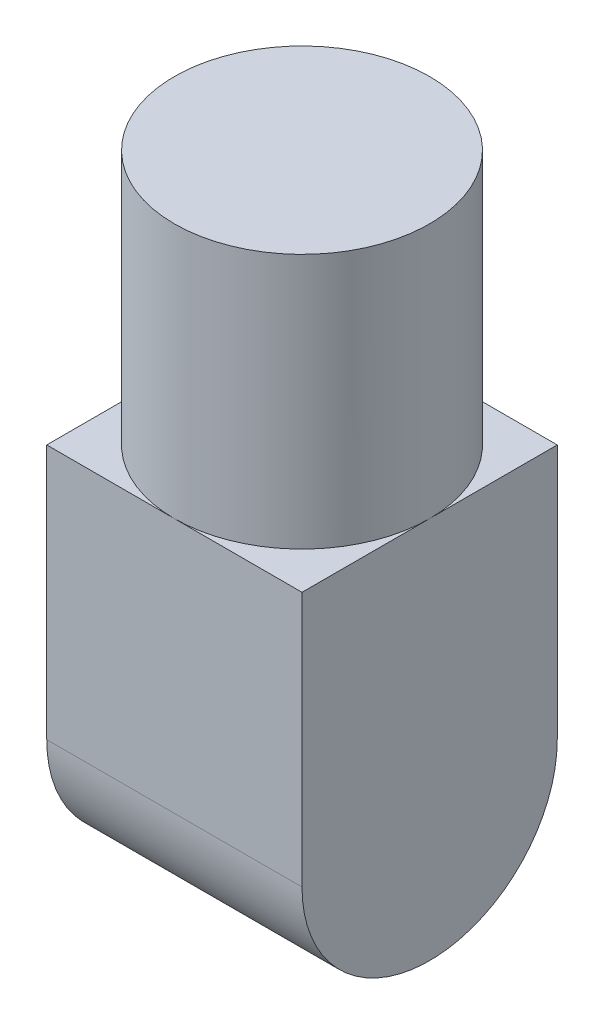
SolidWorks part; units mm, degrees
ref_plane "Front Plane" through (0, 0, 0) normal (0, 0, 1) x (1, 0, 0)
ref_plane "Top Plane" through (0, 0, 0) normal (0, 1, 0) x (1, 0, 0)
ref_plane "Right Plane" through (0, 0, 0) normal (1, 0, 0) x (0, 0, -1)
sketch "Sketch1" plane through (0, 0, 0) normal (1, 0, 0) x (0, 0, -1)
  line L2 (-40, -40) -> (-40, 40)
  line L3 (-40, 40) -> (40, 40)
  line L4 (40, -40) -> (40, 40)
  line L5 (-40, -40) -> (40, 40) construction
  line L6 (-40, 40) -> (40, -40) construction
  arc A0 (-40, -40) -> (40, -40) centre (0, -40) ccw
  point P0 (0, 0)
  dimension "D1" = 80
  dimension "D2" = 80
extrude "Boss-Extrude1" add sketch "Sketch1" along normal blind 80
sketch "Sketch2" plane through (0, 40, 0) normal (0, 1, 0) x (1, 0, 0)
  circle A0 centre (40, 0) radius 40
extrude "Boss-Extrude2" add sketch "Sketch2" along normal blind 80
